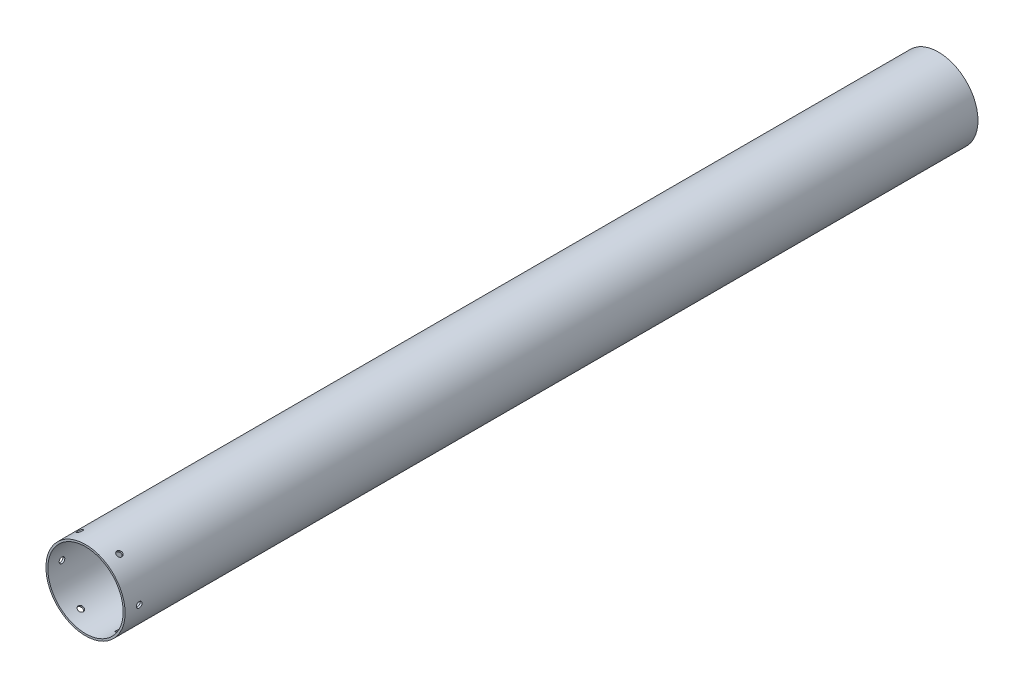
SolidWorks part; units mm, degrees
other "DetailItem1"
other "DetailItem2"
material "Default"
ref_plane "Front Plane" through (0, 0, 0) normal (0, 0, 1) x (1, 0, 0)
ref_plane "Top Plane" through (0, 0, 0) normal (0, 1, 0) x (1, 0, 0)
ref_plane "Right Plane" through (0, 0, 0) normal (1, 0, 0) x (0, 0, -1)
sketch "Sketch1" plane through (0, 0, 0) normal (1, 0, 0) x (0, 0, -1)
  line L0 (-452.5, 0) -> (452.5, 0) construction
  point P4 (0, 0)
  dimension "D1" = 905
ref_plane "Plane1" through (0, 0, 452.5) normal (0, 0, 1) x (1, 0, 0)
sketch "Sketch3" plane through (0, 0, 452.5) normal (0, 0, 1) x (1, 0, 0)
  circle A0 centre (0, 0) radius 42
  circle A1 centre (0, 0) radius 40
  dimension "D1" = 84
  dimension "D2" = 2
extrude "Boss-Extrude1" add sketch "Sketch3" against normal up to vertex (905 mm away) up to point (0, 0, -452.5)
ref_plane "Bolt Attachment" through (42, 0, 0) normal (1, 0, 0) x (0, 0, -1)
sketch "Sketch4" plane through (42, 0, 0) normal (1, 0, 0) x (0, 0, -1)
  line L0 (-452.5, 0) -> (-437.5, 0) construction
  line L1 (-452.5, 42) -> (-452.5, -42) construction
  circle A0 centre (-437.5, 0) radius 3
  dimension "D2" = 6
  dimension "D1" = 15
extrude "Cut-Extrude1" cut sketch "Sketch4" against normal up to surface (2 mm away) up to face at (40, 0, -452.5)
pattern_circular "CirPattern1" count 6 over 360 about axis through (0, 0, 452.5) along (0, 0, 1) of "Cut-Extrude1"
